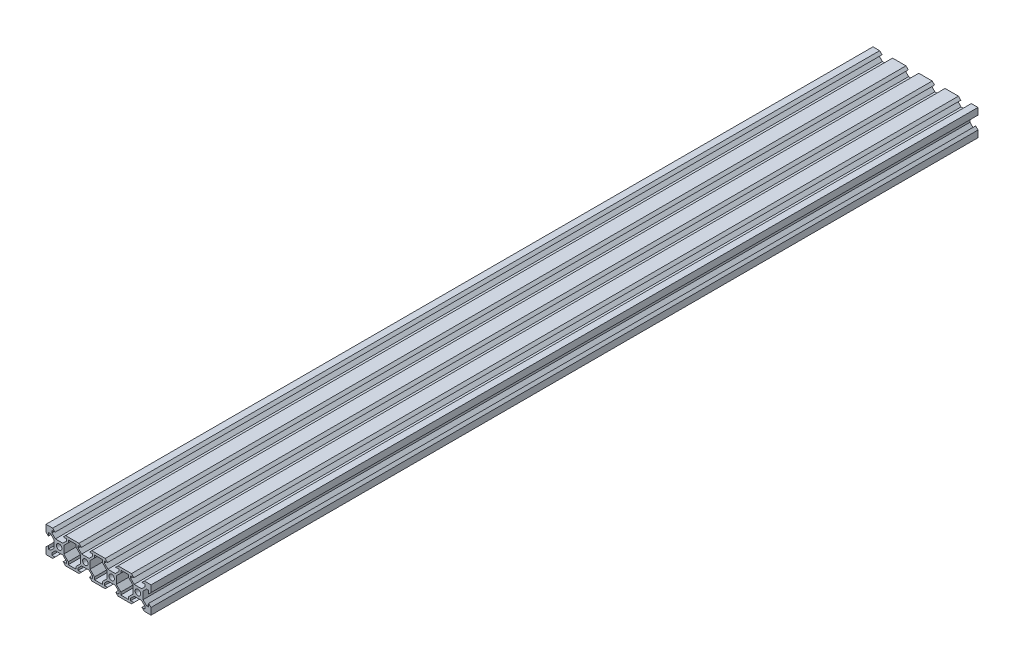
SolidWorks part; units mm, degrees
ref_plane "Plan de face" through (0, 0, 0) normal (0, 0, 1) x (1, 0, 0)
ref_plane "Plan de dessus" through (0, 0, 0) normal (0, 1, 0) x (1, 0, 0)
ref_plane "Plan de droite" through (0, 0, 0) normal (1, 0, 0) x (0, 0, -1)
sketch "Esquisse1" plane through (0, 0, 0) normal (0, 0, 1) x (1, 0, 0)
  line L45 (-65.6277, 8.2661) -> (14.3723, 8.2661)
  line L46 (-65.6277, 8.2661) -> (-65.6277, -11.7339)
  line L47 (-65.6277, -11.7339) -> (14.3723, -11.7339)
  line L48 (14.3723, 8.2661) -> (14.3723, -11.7339)
  dimension "D1" = 80
  dimension "D2" = 20
extrude "Boss.-Extru.1" add sketch "Esquisse1" along normal blind 630
sketch "Esquisse2" plane through (0, 0, 0) normal (0, 0, -1) x (-1, 0, 0)
  line L0 (-14.3723, -11.7339) -> (-14.3723, 8.2661) construction
  line L2 (50.7277, 8.2661) -> (60.5277, 8.2661)
  line L3 (-14.3723, 8.2661) -> (65.6277, 8.2661) construction
  line L4 (60.5277, 8.2661) -> (58.7277, 6.4661)
  line L5 (58.7277, 6.4661) -> (61.1277, 6.4661)
  line L6 (61.1277, 6.4661) -> (61.1277, 4.8261)
  line L7 (61.1277, 4.8261) -> (58.4677, 2.1661)
  line L8 (58.4677, 2.1661) -> (52.7877, 2.1661)
  line L9 (52.7877, 2.1661) -> (50.1277, 4.8261)
  line L10 (50.1277, 4.8261) -> (50.1277, 6.4661)
  line L11 (50.1277, 6.4661) -> (52.5277, 6.4661)
  line L12 (52.5277, 6.4661) -> (50.7277, 8.2661)
  line L43 (65.6277, 8.2661) -> (65.6277, -11.7339) construction
  line L44 (65.6277, 3.1661) -> (65.6277, -6.6339)
  line L45 (65.6277, -6.6339) -> (63.8277, -4.8339)
  line L46 (63.8277, -4.8339) -> (63.8277, -7.2339)
  line L47 (63.8277, -7.2339) -> (62.1877, -7.2339)
  line L48 (62.1877, -7.2339) -> (59.5277, -4.5739)
  line L49 (59.5277, -4.5739) -> (59.5277, 1.1061)
  line L50 (59.5277, 1.1061) -> (62.1877, 3.7661)
  line L51 (62.1877, 3.7661) -> (63.8277, 3.7661)
  line L52 (63.8277, 3.7661) -> (63.8277, 1.3661)
  line L53 (63.8277, 1.3661) -> (65.6277, 3.1661)
  line L54 (60.5277, -11.7339) -> (50.7277, -11.7339)
  line L55 (50.7277, -11.7339) -> (52.5277, -9.9339)
  line L56 (52.5277, -9.9339) -> (50.1277, -9.9339)
  line L57 (50.1277, -9.9339) -> (50.1277, -8.2939)
  line L58 (50.1277, -8.2939) -> (52.7877, -5.6339)
  line L59 (52.7877, -5.6339) -> (58.4677, -5.6339)
  line L60 (58.4677, -5.6339) -> (61.1277, -8.2939)
  line L61 (61.1277, -8.2939) -> (61.1277, -9.9339)
  line L62 (61.1277, -9.9339) -> (58.7277, -9.9339)
  line L63 (58.7277, -9.9339) -> (60.5277, -11.7339)
  line L64 (55.6277, -1.7339) -> (58.4677, 2.1661) construction
  line L65 (55.6277, -1.7339) -> (59.5277, -4.5739) construction
  line L66 (30.7277, 8.2661) -> (40.5277, 8.2661)
  line L67 (40.5277, 8.2661) -> (38.7277, 6.4661)
  line L68 (38.7277, 6.4661) -> (41.1277, 6.4661)
  line L69 (41.1277, 6.4661) -> (41.1277, 4.8261)
  line L70 (41.1277, 4.8261) -> (38.4677, 2.1661)
  line L71 (38.4677, 2.1661) -> (32.7877, 2.1661)
  line L72 (32.7877, 2.1661) -> (30.1277, 4.8261)
  line L73 (30.1277, 4.8261) -> (30.1277, 6.4661)
  line L74 (30.1277, 6.4661) -> (32.5277, 6.4661)
  line L75 (32.5277, 6.4661) -> (30.7277, 8.2661)
  line L76 (40.5277, -11.7339) -> (30.7277, -11.7339)
  line L77 (30.7277, -11.7339) -> (32.5277, -9.9339)
  line L78 (32.5277, -9.9339) -> (30.1277, -9.9339)
  line L79 (30.1277, -9.9339) -> (30.1277, -8.2939)
  line L80 (30.1277, -8.2939) -> (32.7877, -5.6339)
  line L81 (32.7877, -5.6339) -> (38.4677, -5.6339)
  line L82 (38.4677, -5.6339) -> (41.1277, -8.2939)
  line L83 (41.1277, -8.2939) -> (41.1277, -9.9339)
  line L84 (41.1277, -9.9339) -> (38.7277, -9.9339)
  line L85 (38.7277, -9.9339) -> (40.5277, -11.7339)
  line L86 (35.6277, -1.7339) -> (38.4677, 2.1661) construction
  line L87 (10.7277, 8.2661) -> (20.5277, 8.2661)
  line L88 (20.5277, 8.2661) -> (18.7277, 6.4661)
  line L89 (18.7277, 6.4661) -> (21.1277, 6.4661)
  line L90 (21.1277, 6.4661) -> (21.1277, 4.8261)
  line L91 (21.1277, 4.8261) -> (18.4677, 2.1661)
  line L92 (18.4677, 2.1661) -> (12.7877, 2.1661)
  line L93 (12.7877, 2.1661) -> (10.1277, 4.8261)
  line L94 (10.1277, 4.8261) -> (10.1277, 6.4661)
  line L95 (10.1277, 6.4661) -> (12.5277, 6.4661)
  line L96 (12.5277, 6.4661) -> (10.7277, 8.2661)
  line L97 (20.5277, -11.7339) -> (10.7277, -11.7339)
  line L98 (10.7277, -11.7339) -> (12.5277, -9.9339)
  line L99 (12.5277, -9.9339) -> (10.1277, -9.9339)
  line L100 (10.1277, -9.9339) -> (10.1277, -8.2939)
  line L101 (10.1277, -8.2939) -> (12.7877, -5.6339)
  line L102 (12.7877, -5.6339) -> (18.4677, -5.6339)
  line L103 (18.4677, -5.6339) -> (21.1277, -8.2939)
  line L104 (21.1277, -8.2939) -> (21.1277, -9.9339)
  line L105 (21.1277, -9.9339) -> (18.7277, -9.9339)
  line L106 (18.7277, -9.9339) -> (20.5277, -11.7339)
  line L107 (15.6277, -1.7339) -> (18.4677, 2.1661) construction
  line L108 (-9.2723, 8.2661) -> (0.5277, 8.2661)
  line L109 (0.5277, 8.2661) -> (-1.2723, 6.4661)
  line L110 (-1.2723, 6.4661) -> (1.1277, 6.4661)
  line L111 (1.1277, 6.4661) -> (1.1277, 4.8261)
  line L112 (1.1277, 4.8261) -> (-1.5323, 2.1661)
  line L113 (-1.5323, 2.1661) -> (-7.2123, 2.1661)
  line L114 (-7.2123, 2.1661) -> (-9.8723, 4.8261)
  line L115 (-9.8723, 4.8261) -> (-9.8723, 6.4661)
  line L116 (-9.8723, 6.4661) -> (-7.4723, 6.4661)
  line L117 (-7.4723, 6.4661) -> (-9.2723, 8.2661)
  line L118 (0.5277, -11.7339) -> (-9.2723, -11.7339)
  line L119 (-9.2723, -11.7339) -> (-7.4723, -9.9339)
  line L120 (-7.4723, -9.9339) -> (-9.8723, -9.9339)
  line L121 (-9.8723, -9.9339) -> (-9.8723, -8.2939)
  line L122 (-9.8723, -8.2939) -> (-7.2123, -5.6339)
  line L123 (-7.2123, -5.6339) -> (-1.5323, -5.6339)
  line L124 (-1.5323, -5.6339) -> (1.1277, -8.2939)
  line L125 (1.1277, -8.2939) -> (1.1277, -9.9339)
  line L126 (1.1277, -9.9339) -> (-1.2723, -9.9339)
  line L127 (-1.2723, -9.9339) -> (0.5277, -11.7339)
  line L128 (-4.3723, -1.7339) -> (-1.5323, 2.1661) construction
  line L129 (-14.3723, -6.6339) -> (-14.3723, 3.1661)
  line L130 (-14.3723, 3.1661) -> (-12.5723, 1.3661)
  line L131 (-12.5723, 1.3661) -> (-12.5723, 3.7661)
  line L132 (-12.5723, 3.7661) -> (-10.9323, 3.7661)
  line L133 (-10.9323, 3.7661) -> (-8.2723, 1.1061)
  line L134 (-8.2723, 1.1061) -> (-8.2723, -4.5739)
  line L135 (-8.2723, -4.5739) -> (-10.9323, -7.2339)
  line L136 (-10.9323, -7.2339) -> (-12.5723, -7.2339)
  line L137 (-12.5723, -7.2339) -> (-12.5723, -4.8339)
  line L138 (-12.5723, -4.8339) -> (-14.3723, -6.6339)
  line L139 (-4.3723, -1.7339) -> (-1.5323, 2.1661) construction
  line L140 (-4.3723, -1.7339) -> (-8.2723, 1.1061) construction
  circle A0 centre (55.6277, -1.7339) radius 2.1
  circle A1 centre (35.6277, -1.7339) radius 2.1
  circle A2 centre (15.6277, -1.7339) radius 2.1
  circle A3 centre (-4.3723, -1.7339) radius 2.1
  point P5 (-14.3723, -1.7339)
  point P17 (55.6277, 2.1661)
  point P54 (10.6277, 13.2661)
  dimension "D1" = 4.2
  dimension "D2" = 135
  dimension "D3" = 1.64
  dimension "D4" = 5.68
  dimension "D5" = 1.8
  dimension "D6" = 6.2
  dimension "D7" = 11
  dimension "D8" = 10
  dimension "D10" = 90
  dimension "D13" = 90
  dimension "D11" = 4
  dimension "D9" = 3
  dimension "D12" = 2
extrude "Enlèv. mat.-Extru.1" cut sketch "Esquisse2" against normal up to next
sketch "Esquisse3" plane through (0, 0, 0) normal (0, 0, -1) x (-1, 0, 0)
  line L0 (2.6183, 6.4661) -> (8.6372, 6.4661)
  line L1 (8.6372, 6.4661) -> (8.6372, 4.5061)
  line L2 (8.6372, 4.5061) -> (12.0372, 1.1061)
  line L3 (12.0372, 1.1061) -> (12.0372, -4.5739)
  line L4 (12.0372, -4.5739) -> (8.6372, -7.9739)
  line L5 (8.6372, -7.9739) -> (8.6372, -9.9339)
  line L6 (8.6372, -9.9339) -> (2.6183, -9.9339)
  line L7 (2.6183, -9.9339) -> (2.6183, -7.9739)
  line L8 (2.6183, -7.9739) -> (-0.7817, -4.5739)
  line L9 (-0.7817, -4.5739) -> (-0.7817, 1.1061)
  line L10 (-0.7817, 1.1061) -> (2.6183, 4.5061)
  line L11 (2.6183, 4.5061) -> (2.6183, 6.4661)
  line L12 (0.5277, 8.2661) -> (10.7277, 8.2661) construction
  line L13 (-1.2723, -9.9339) -> (1.1277, -9.9339) construction
  line L14 (1.1277, 6.4661) -> (-1.2723, 6.4661) construction
  line L15 (22.6183, 6.4661) -> (28.6372, 6.4661)
  line L16 (28.6372, 6.4661) -> (28.6372, 4.5061)
  line L17 (28.6372, 4.5061) -> (32.0372, 1.1061)
  line L18 (32.0372, 1.1061) -> (32.0372, -4.5739)
  line L19 (32.0372, -4.5739) -> (28.6372, -7.9739)
  line L20 (28.6372, -7.9739) -> (28.6372, -9.9339)
  line L21 (28.6372, -9.9339) -> (22.6183, -9.9339)
  line L22 (22.6183, -9.9339) -> (22.6183, -7.9739)
  line L23 (22.6183, -7.9739) -> (19.2183, -4.5739)
  line L24 (19.2183, -4.5739) -> (19.2183, 1.1061)
  line L25 (19.2183, 1.1061) -> (22.6183, 4.5061)
  line L26 (22.6183, 4.5061) -> (22.6183, 6.4661)
  line L27 (42.6183, 6.4661) -> (48.6372, 6.4661)
  line L28 (48.6372, 6.4661) -> (48.6372, 4.5061)
  line L29 (48.6372, 4.5061) -> (52.0372, 1.1061)
  line L30 (52.0372, 1.1061) -> (52.0372, -4.5739)
  line L31 (52.0372, -4.5739) -> (48.6372, -7.9739)
  line L32 (48.6372, -7.9739) -> (48.6372, -9.9339)
  line L33 (48.6372, -9.9339) -> (42.6183, -9.9339)
  line L34 (42.6183, -9.9339) -> (42.6183, -7.9739)
  line L35 (42.6183, -7.9739) -> (39.2183, -4.5739)
  line L36 (39.2183, -4.5739) -> (39.2183, 1.1061)
  line L37 (39.2183, 1.1061) -> (42.6183, 4.5061)
  line L38 (42.6183, 4.5061) -> (42.6183, 6.4661)
  circle A0 centre (-4.3723, -1.7339) radius 2.1 construction
  circle A1 centre (-4.3723, -1.7339) radius 2.1 construction
  point P13 (5.6277, 6.4661)
  point P16 (5.6277, 8.2661)
  point P28 (-0.7817, -1.7339)
  point P29 (12.0372, -1.7339)
  dimension "D1" = 5.68
  dimension "D2" = 1.96
  dimension "D3" = 3
extrude "Enlèv. mat.-Extru.2" cut sketch "Esquisse3" against normal up to next
